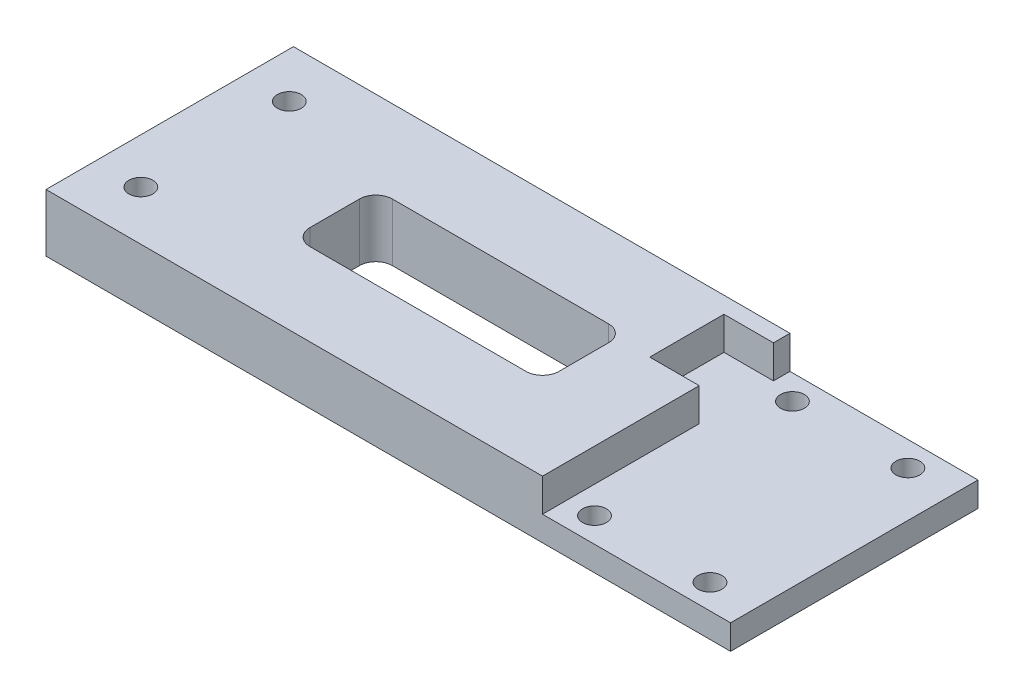
SolidWorks part; units mm, degrees
ref_plane "前视基准面" through (0, 0, 0) normal (0, 0, 1) x (1, 0, 0)
ref_plane "上视基准面" through (0, 0, 0) normal (0, 1, 0) x (1, 0, 0)
ref_plane "右视基准面" through (0, 0, 0) normal (1, 0, 0) x (0, 0, -1)
other "Configuration Table"
sketch "草图1" plane through (0, 0, 0) normal (0, 1, 0) x (1, 0, 0)
  line L1 (0, 0) -> (-88, 0)
  line L2 (0, 0) -> (0, 30)
  line L3 (0, 30) -> (-88, 30)
  line L4 (-88, 0) -> (-88, 30)
  dimension "D1" = 88
  dimension "D2" = 30
extrude "凸台-拉伸1" add sketch "草图1" along normal blind 3
sketch "草图2" plane through (0, 3, 0) normal (0, 1, 0) x (1, 0, 0)
  line L0 (-88, 0) -> (0, 0) construction
  line L1 (0, 30) -> (-27.8, 30)
  line L2 (0, 30) -> (0, 0)
  line L3 (0, 0) -> (-27.8, 0)
  line L4 (-27.8, 30) -> (-27.8, 0)
  dimension "D1" = 27.8
extrude "切除-拉伸1" cut sketch "草图2" against normal blind 1
sketch "草图3" plane through (0, 2, 0) normal (0, 1, 0) x (1, 0, 0)
  line L0 (-27.5, 30) -> (-27.5, 27) construction
  line L3 (-27.5, 27) -> (-24.5, 27) construction
  line L4 (-24.5, 27) -> (-24.5, 3) construction
  line L5 (-24.5, 3) -> (-10.5, 3) construction
  line L6 (-10.5, 3) -> (-10.5, 27) construction
  circle A4 centre (-24.5, 27) radius 1.45
  circle A5 centre (-24.5, 3) radius 1.45
  circle A6 centre (-10.5, 3) radius 1.45
  circle A7 centre (-10.5, 27) radius 1.45
  dimension "D6" = 2.9
  dimension "D1" = 3
  dimension "D2" = 3
  dimension "D3" = 24
  dimension "D4" = 14
  dimension "D5" = 24
extrude "切除-拉伸2" cut sketch "草图3" against normal blind 11
sketch "草图4" plane through (0, 3, 0) normal (0, 1, 0) x (1, 0, 0)
  line L0 (-88, 24) -> (-82.5, 24) construction
  line L2 (-27.8, 30) -> (-88, 30) construction
  line L3 (-88, 15) -> (-85.0043, 15) construction
  line L4 (-88, 30) -> (-88, 0) construction
  circle A0 centre (-82.5, 24) radius 1.45
  circle A1 centre (-82.5, 6) radius 1.45
  dimension "D2" = 2.9
  dimension "D1" = 5.5
  dimension "D3" = 6
extrude "切除-拉伸4" cut sketch "草图4" against normal blind 11
sketch "草图5" plane through (0, 3, 0) normal (0, 1, 0) x (1, 0, 0)
  line L0 (-88, 0) -> (-27.8, 0) construction
  line L1 (-68, 20) -> (-37.8, 20)
  line L2 (-68, 20) -> (-68, 10)
  line L3 (-68, 10) -> (-37.8, 10)
  line L4 (-37.8, 20) -> (-37.8, 10)
  line L5 (-27.8, 30) -> (-88, 30) construction
  line L6 (-27.8, 30) -> (-27.8, 0) construction
  line L7 (-88, 30) -> (-88, 0) construction
  dimension "D1" = 10
  dimension "D2" = 10
  dimension "D3" = 10
  dimension "D4" = 20
extrude "切除-拉伸5" cut sketch "草图5" against normal blind 11
fillet "圆角1" radius 2 4 edges at (-68, 1.5, -10) (-37.8, 1.5, -10) (-37.8, 1.5, -20) (-68, 1.5, -20)
sketch "草图6" plane through (0, 0, 0) normal (0, -1, 0) x (1, 0, 0)
  line L0 (0, -30) -> (-88, -30) construction
  line L1 (0, 0) -> (-5, 0)
  line L2 (0, 0) -> (0, -30)
  line L3 (0, -30) -> (-5, -30)
  line L4 (-5, 0) -> (-5, -30)
  dimension "D1" = 5
extrude "切除-拉伸6" cut sketch "草图6" against normal blind 10
sketch "草图7" plane through (0, 2, 0) normal (0, 1, 0) x (1, 0, 0)
  line L4 (-27.8, 0) -> (-5, 0)
  line L5 (-5, 0) -> (-5, 30)
  line L6 (-5, 30) -> (-27.8, 30)
  line L7 (-27.8, 30) -> (-27.8, 0)
  line L8 (-27.8, 0) -> (-5, 0)
  line L9 (-5, 0) -> (-5, 30)
  line L10 (-5, 30) -> (-27.8, 30)
  line L11 (-27.8, 30) -> (-27.8, 0)
  circle A0 centre (-24.5, 27) radius 1.45 construction
  circle A1 centre (-10.5, 3) radius 1.45 construction
  circle A2 centre (-10.5, 3) radius 1.45
  circle A3 centre (-24.5, 27) radius 1.45
  circle A4 centre (-10.5, 27) radius 1.45 construction
  circle A5 centre (-24.5, 3) radius 1.45 construction
  circle A6 centre (-10.5, 27) radius 1.45
  circle A7 centre (-24.5, 3) radius 1.45
  dimension "D1" = 0
sketch "草图9" plane through (0, 3, 0) normal (0, 1, 0) x (1, 0, 0)
  line L0 (-39.8, 20) -> (-66, 20) construction
  line L1 (-66, 10) -> (-39.8, 10) construction
  line L2 (-68, 18) -> (-68, 12) construction
  line L3 (-37.8, 12) -> (-37.8, 18) construction
  line L4 (-27.8, 0) -> (-27.8, 30)
  line L5 (-27.8, 30) -> (-88, 30)
  line L6 (-88, 30) -> (-88, 0)
  line L7 (-88, 0) -> (-27.8, 0)
  line L8 (-27.8, 0) -> (-27.8, 30)
  line L9 (-27.8, 30) -> (-88, 30)
  line L10 (-88, 30) -> (-88, 0)
  line L11 (-88, 0) -> (-27.8, 0)
  line L12 (-37.8, 12) -> (-37.8, 18)
  line L13 (-68, 18) -> (-68, 12)
  line L14 (-66, 10) -> (-39.8, 10)
  line L15 (-39.8, 20) -> (-66, 20)
  circle A0 centre (-82.5, 24) radius 1.45 construction
  circle A1 centre (-82.5, 6) radius 1.45 construction
  arc A2 (-37.8, 18) -> (-39.8, 20) centre (-39.8, 18) ccw construction
  arc A3 (-66, 20) -> (-68, 18) centre (-66, 18) ccw construction
  arc A4 (-68, 12) -> (-66, 10) centre (-66, 12) ccw construction
  arc A5 (-39.8, 10) -> (-37.8, 12) centre (-39.8, 12) ccw construction
  arc A6 (-39.8, 10) -> (-37.8, 12) centre (-39.8, 12) ccw
  arc A7 (-68, 12) -> (-66, 10) centre (-66, 12) ccw
  arc A8 (-66, 20) -> (-68, 18) centre (-66, 18) ccw
  arc A9 (-37.8, 18) -> (-39.8, 20) centre (-39.8, 18) ccw
  circle A10 centre (-82.5, 6) radius 1.45
  circle A11 centre (-82.5, 24) radius 1.45
  dimension "D1" = 0
extrude "凸台-拉伸4" add sketch "草图9" along normal blind 4
extrude "凸台-拉伸5" add sketch "草图7" along normal blind 1
sketch "草图11" plane through (-27.8, 0, 0) normal (1, 0, 0) x (0, 0, -1)
  line L0 (0, 3) -> (30, 3) construction
  line L6 (30, 3) -> (15, 3)
  line L7 (30, 3) -> (30, 7)
  line L8 (30, 7) -> (15, 7)
  line L9 (15, 3) -> (15, 7)
extrude "切除-拉伸8" cut sketch "草图11" against normal blind 6
sketch "草图12" plane through (-33.8, 0, 0) normal (1, 0, 0) x (0, 0, -1)
  line L0 (15, 3) -> (30, 3) construction
  line L1 (30, 7) -> (28, 7)
  line L2 (30, 7) -> (30, 3)
  line L3 (30, 3) -> (28, 3)
  line L4 (28, 7) -> (28, 3)
  dimension "D1" = 2
extrude "凸台-拉伸6" add sketch "草图12" along normal blind 6
sketch "草图13" plane through (0, 0, -15) normal (0, 0, -1) x (-1, 0, 0)
  line L4 (27.8, 7) -> (27.8, 3)
  line L5 (27.8, 3) -> (33.8, 3)
  line L6 (33.8, 3) -> (33.8, 7)
  line L7 (33.8, 7) -> (27.8, 7)
  line L8 (27.8, 7) -> (27.8, 3)
  line L9 (27.8, 3) -> (33.8, 3)
  line L10 (33.8, 3) -> (33.8, 7)
  line L11 (33.8, 7) -> (27.8, 7)
  dimension "D1" = 0
extrude "凸台-拉伸7" add sketch "草图13" along normal blind 4
sketch "草图14" plane through (0, 0, 0) normal (0, -1, 0) x (1, 0, 0)
  circle A0 centre (-82.5, -6) radius 4
  circle A1 centre (-82.5, -24) radius 4
  dimension "D1" = 8
  dimension "D2" = 8
extrude "切除-拉伸9" cut sketch "草图14" against normal blind 4
